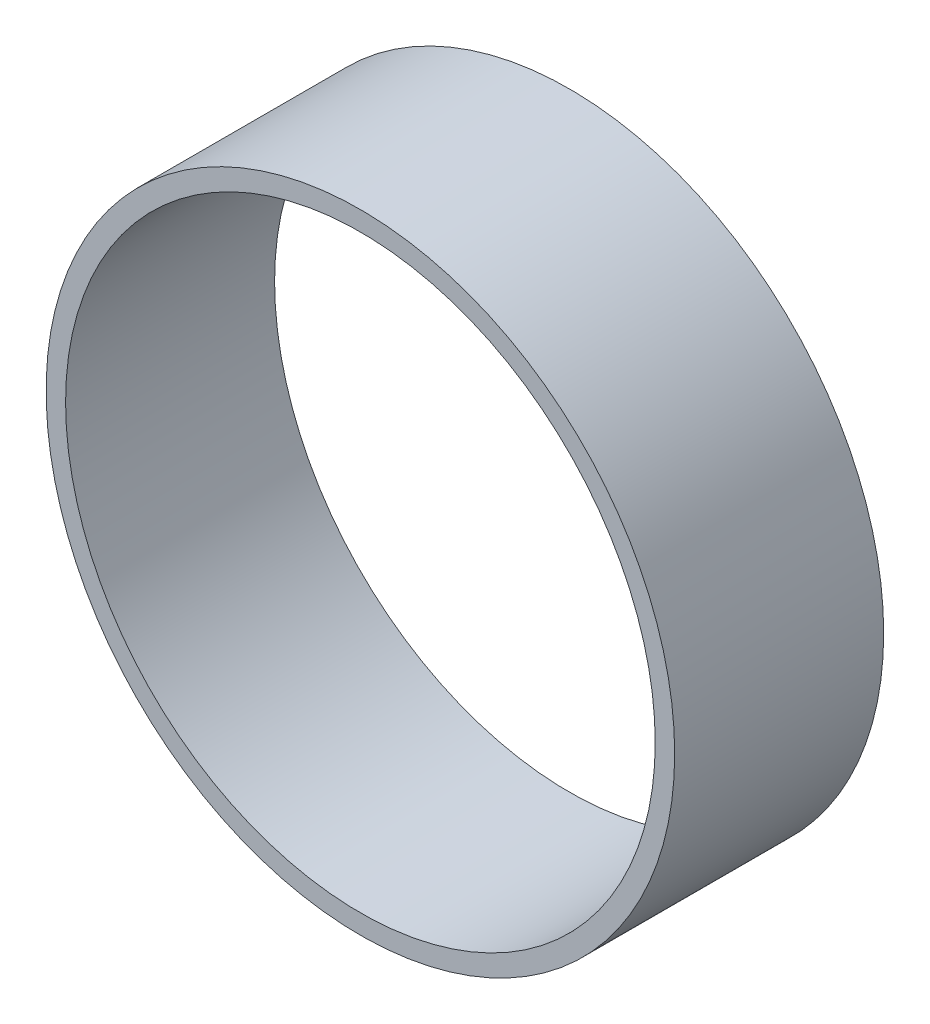
SolidWorks part; units mm, degrees
ref_plane "前视基准面" through (0, 0, 0) normal (0, 0, 1) x (1, 0, 0)
ref_plane "上视基准面" through (0, 0, 0) normal (0, 1, 0) x (1, 0, 0)
ref_plane "右视基准面" through (0, 0, 0) normal (1, 0, 0) x (0, 0, -1)
other "Configuration Table"
sketch "草图1" plane through (0, 0, 0) normal (0, 0, 1) x (1, 0, 0)
  circle A0 centre (0, 0) radius 15.15
  dimension "D1" = 30.3
extrude "拉伸-薄壁1" add sketch "草图1" along normal blind 10.74 thin
